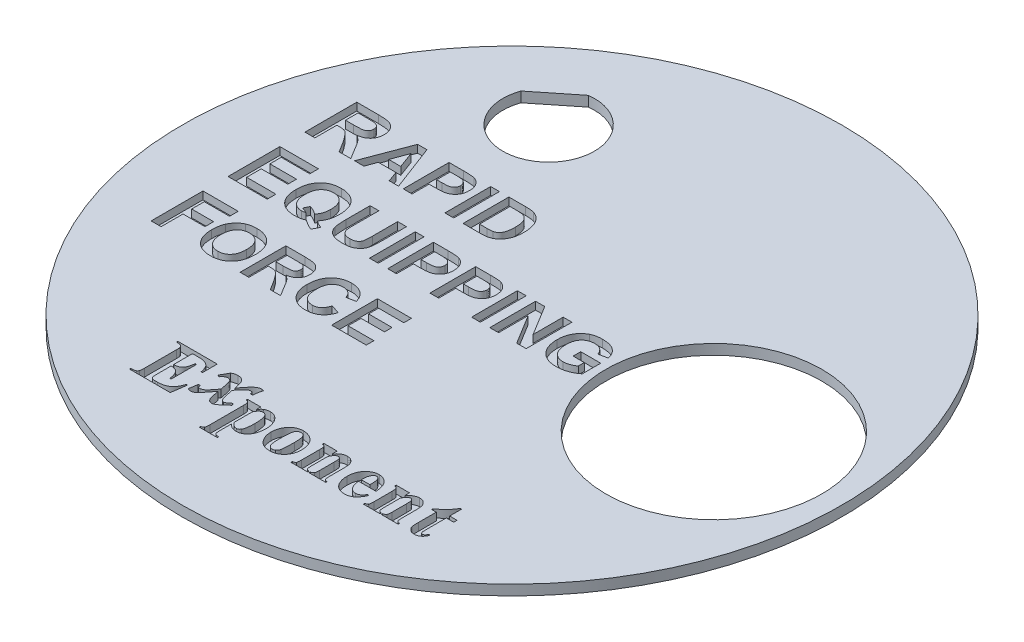
SolidWorks part; units mm, degrees
material "6061 Alloy"
ref_plane "Front Plane" through (0, 0, 0) normal (0, 0, 1) x (1, 0, 0)
ref_plane "Top Plane" through (0, 0, 0) normal (0, 1, 0) x (1, 0, 0)
ref_plane "Right Plane" through (0, 0, 0) normal (1, 0, 0) x (0, 0, -1)
sketch "Sketch1" plane through (0, 0, 0) normal (0, 1, 0) x (1, 0, 0)
  circle A0 centre (0, 0) radius 20.828
  dimension "D1" = 41.656
extrude "Boss-Extrude1" add sketch "Sketch1" along normal blind 1.27
sketch "Sketch2" plane through (0, 1.27, 0) normal (0, 1, 0) x (1, 0, 0)
  circle A0 centre (0, 0) radius 20.32
  circle A1 centre (0, 0) radius 20.828
  circle A2 centre (0, 0) radius 20.828 construction
  dimension "D1" = 0.508
extrude "Cut-Extrude2" cut sketch "Sketch2" against normal blind 0.635
sketch "Sketch3" plane through (0, 1.27, 0) normal (0, 1, 0) x (1, 0, 0)
  line L0 (20.828, 3.7545) -> (20.828, -12.2477) construction
  line L1 (0, 0) -> (20.828, 0) construction
  line L2 (18.6677, 2.8354) -> (18.6677, -2.8354)
  line L3 (9.3332, 2.8354) -> (9.3332, -2.8354)
  arc A0 (9.3332, -2.8354) -> (18.6677, -2.8354) centre (14.0005, 0) ccw
  arc A2 (18.6677, 2.8354) -> (9.3332, 2.8354) centre (14.0005, 0) ccw
  circle A3 centre (0, 0) radius 20.828 construction
  dimension "D1" = 10.922
  dimension "D3" = 4.6672
  dimension "D2" = 14.0005
extrude "Cut-Extrude3" cut sketch "Sketch3" against normal through all
chamfer "Chamfer1" [suppressed] distance 0.127 angle 45
sketch "Sketch12" plane through (0, 0, 0) normal (0, -1, 0) x (1, 0, 0)
  line L1 (-7.6581, 18.2626) -> (5.6769, 18.2626)
  line L2 (-9.2456, 16.6751) -> (-9.2456, 3.3401)
  line L3 (-7.6581, 1.7526) -> (5.6769, 1.7526)
  line L4 (7.2644, 16.6751) -> (7.2644, 3.3401)
  line L5 (-9.2456, 18.2626) -> (7.2644, 1.7526) construction
  line L6 (-9.2456, 1.7526) -> (7.2644, 18.2626) construction
  arc A0 (-9.2456, 16.6751) -> (-7.6581, 18.2626) centre (-7.6581, 16.6751) cw
  arc A1 (-7.6581, 1.7526) -> (-9.2456, 3.3401) centre (-7.6581, 3.3401) cw
  arc A2 (7.2644, 3.3401) -> (5.6769, 1.7526) centre (5.6769, 3.3401) cw
  arc A3 (7.2644, 16.6751) -> (5.6769, 18.2626) centre (5.6769, 16.6751) ccw
  point P0 (-0.9906, 10.0076)
  dimension "D3" = 16.51
  dimension "D4" = 1.5875
  dimension "D1" = 10.0076
  dimension "D2" = 0.9906
extrude "Cut-Extrude4" [suppressed] cut sketch "Sketch12" against normal blind 0.508
sketch "Sketch13" plane through (0, 0, 0) normal (0, -1, 0) x (1, 0, 0)
  line L0 (-13.1479, -13.7739) -> (-10.5519, -15.8507)
  line L1 (-16.7984, -13.2341) -> (-6.871, -21.176) construction
  line L2 (-13.0111, -16.2639) -> (0, 0) construction
  arc A0 (-10.5519, -15.8507) -> (-13.1479, -13.7739) centre (-10.16, -12.7) ccw
  circle A1 centre (0, 0) radius 20.828 construction
  circle A2 centre (0, 0) radius 20.828 construction
  dimension "D3" = 6.35
  dimension "D4" = 2.7051
  dimension "D1" = 12.7
  dimension "D2" = 10.16
extrude "Cut-Extrude5" cut sketch "Sketch13" against normal through all
sketch "Sketch16" plane through (0, 1.27, 0) normal (0, 1, 0) x (1, 0, 0)
  circle A0 centre (0, 0) radius 20.32
  circle A1 centre (0, 0) radius 22.86
  circle A2 centre (0, 0) radius 20.32 construction
  dimension "D1" = 45.72
extrude "Boss-Extrude2" add sketch "Sketch16" against normal up to surface (1.27 mm away) up to face at (-10.0132, 0, -12.5165)
sketch "Sketch17" plane through (0, 1.27, 0) normal (0, 1, 0) x (1, 0, 0)
  circle A0 centre (14.0005, 0) radius 7.493
  arc A3 (18.6677, 2.8354) -> (9.3332, 2.8354) centre (14.0005, 0) ccw construction
  dimension "D1" = 14.986
extrude "Cut-Extrude6" cut sketch "Sketch17" against normal through all
sketch "Sketch18" plane through (0, 0, 0) normal (0, -1, 0) x (1, 0, 0)
  circle A0 centre (0, 0) radius 22.86
  circle A1 centre (0, 0) radius 22.86 construction
extrude "Cut-Extrude7" cut sketch "Sketch18" against normal offset from surface (0.5588 mm away) 0.7112 up to face at (14.0005, 1.27, 7.493)
sketch "Sketch20" plane through (0, 1.27, 0) normal (0, 1, 0) x (1, 0, 0)
  line L0 (-18.542, 3.81) -> (-18.542, -1.524) construction
  line L1 (-18.542, -1.524) -> (-18.542, -6.858) construction
  text T0 "R" font "Arial" height in points 14
  text T1 "E" font "Arial" height in points 14
  text T2 "F" font "Arial" height in points 14
  text T3 "APID" font "Arial" height 3.175
  text T4 "QUIPPING" font "Arial" height 3.175
  text T5 "ORCE" font "Arial" height 3.175
  text T6 "E  ponent" font "Times New Roman" height in points 14
  text T7 "x" font "Palatino Linotype" height in points 14
  dimension "D1" = 3.81
  dimension "D2" = 5.334
  dimension "D3" = 18.542
  dimension "D4" = 3.81
  dimension "D5" = 3.302
  dimension "D6" = 2.794
  dimension "D7" = 16.51
  dimension "D8" = 10.16
  dimension "D9" = 3.429
  dimension "D10" = 0.889
extrude "Cut-Extrude8" cut sketch "Sketch20" against normal offset from surface (0.5334 mm away) 0.1778 up to face at (14.0005, 0.5588, 7.493)
